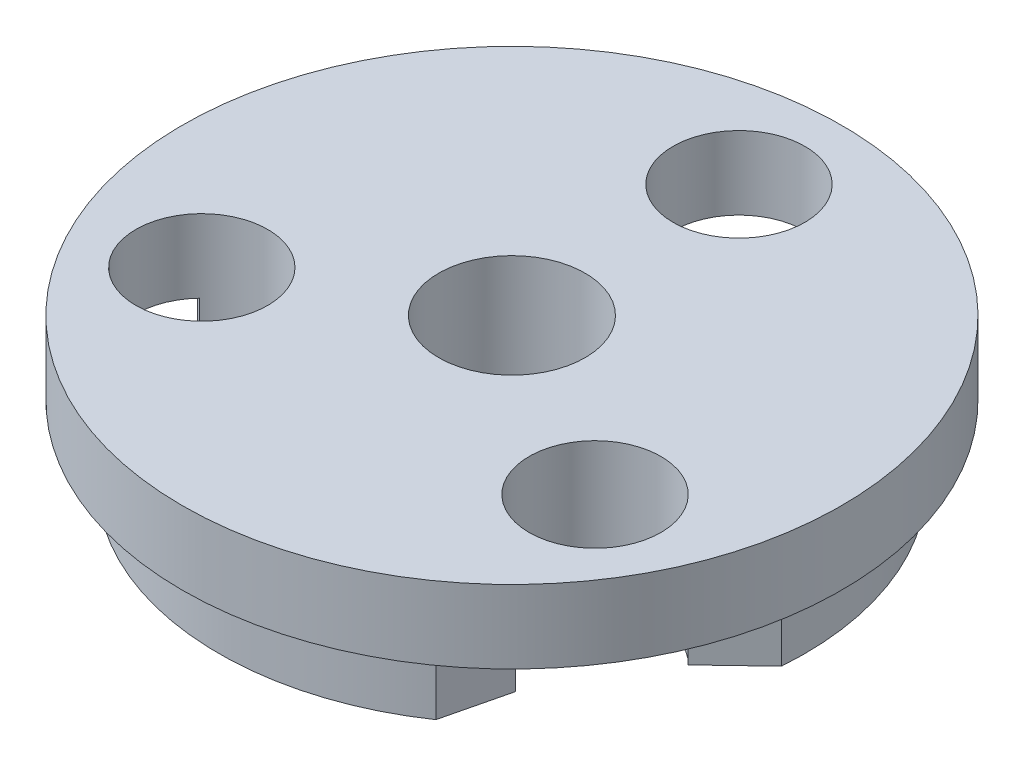
SolidWorks part; units mm, degrees
ref_plane "Front Plane" through (0, 0, 0) normal (0, 0, 1) x (1, 0, 0)
ref_plane "Top Plane" through (0, 0, 0) normal (0, 1, 0) x (1, 0, 0)
ref_plane "Right Plane" through (0, 0, 0) normal (1, 0, 0) x (0, 0, -1)
sketch "Sketch1" plane through (0, 0, 0) normal (0, 1, 0) x (1, 0, 0)
  circle A0 centre (0, 0) radius 22.5
  dimension "D1" = 45
extrude "Boss-Extrude1" add sketch "Sketch1" along normal mid plane 7
sketch "Sketch2" plane through (0, 3.5, 0) normal (0, 1, 0) x (1, 0, 0)
  circle A0 centre (0, 15.5) radius 9
  circle A2 centre (13.4234, -7.75) radius 9
  circle A3 centre (-13.4234, -7.75) radius 9
  point P10 (0, 0)
  dimension "D1" = 18
  dimension "D2" = 3
  dimension "D3" = 15.5
sketch "Sketch7" plane through (0, 3.5, 0) normal (0, 1, 0) x (1, 0, 0)
  circle A0 centre (0, 0) radius 5
  dimension "D1" = 10
extrude "Cut-Extrude1" cut sketch "Sketch2" against normal through all
extrude "Cut-Extrude2" cut sketch "Sketch7" against normal through all
sketch "Sketch8" plane through (0, -3.5, 0) normal (0, -1, 0) x (1, 0, 0)
  circle A0 centre (0, 0) radius 20
  arc A6 (-21.9601, 4.8995) -> (-6.7369, -21.4677) centre (0, 0) ccw
  arc A7 (6.7369, -21.4677) -> (-6.7369, -21.4677) centre (0, -15.5) ccw
  arc A8 (6.7369, -21.4677) -> (21.9601, 4.8995) centre (0, 0) ccw
  arc A9 (15.2232, 16.5682) -> (21.9601, 4.8995) centre (13.4234, 7.75) ccw
  arc A10 (15.2232, 16.5682) -> (-15.2232, 16.5682) centre (0, 0) ccw
  arc A11 (-21.9601, 4.8995) -> (-15.2232, 16.5682) centre (-13.4234, 7.75) ccw
  arc A12 (-21.9601, 4.8995) -> (-6.7369, -21.4677) centre (0, 0) ccw
  arc A13 (6.7369, -21.4677) -> (-6.7369, -21.4677) centre (0, -15.5) ccw
  arc A14 (6.7369, -21.4677) -> (21.9601, 4.8995) centre (0, 0) ccw
  arc A15 (15.2232, 16.5682) -> (21.9601, 4.8995) centre (13.4234, 7.75) ccw
  arc A16 (15.2232, 16.5682) -> (-15.2232, 16.5682) centre (0, 0) ccw
  arc A17 (-21.9601, 4.8995) -> (-15.2232, 16.5682) centre (-13.4234, 7.75) ccw
  circle M7 centre (0, 0) radius 5
  arc M9 (-6.7369, -21.4677) -> (6.7369, -21.4677) centre (0, -15.5) cw
  arc M11 (21.9601, 4.8995) -> (15.2232, 16.5682) centre (13.4234, 7.75) cw
  arc M13 (-15.2232, 16.5682) -> (-21.9601, 4.8995) centre (-13.4234, 7.75) cw
  dimension "D2" = 40
  dimension "D1" = 0
extrude "Boss-Extrude2" add sketch "Sketch8" along normal blind 5 contours A0 M9 M11 M13 M7
sketch "Sketch9" plane through (0, -8.5, 0) normal (0, -1, 0) x (1, 0, 0)
  line L0 (-19.9404, 1.5429) -> (-16.6819, 4.6464)
  line L1 (-12.3649, 12.1237) -> (-11.3064, 16.4975)
  line L4 (11.3064, 16.4975) -> (12.3649, 12.1237)
  line L5 (16.6819, 4.6464) -> (19.9404, 1.5429)
  arc A3 (11.3064, 16.4975) -> (19.9404, 1.5429) centre (13.4234, 7.75) ccw construction
  arc A7 (-19.9404, 1.5429) -> (-11.3064, 16.4975) centre (-13.4234, 7.75) ccw construction
  arc A8 (11.3064, 16.4975) -> (19.9404, 1.5429) centre (13.4234, 7.75) ccw
  arc A9 (-19.9404, 1.5429) -> (-11.3064, 16.4975) centre (-13.4234, 7.75) ccw
  arc A10 (-16.6819, 4.6464) -> (-12.3649, 12.1237) centre (-13.4234, 7.75) ccw
  arc A11 (12.3649, 12.1237) -> (16.6819, 4.6464) centre (13.4234, 7.75) ccw
  dimension "D1" = 9
extrude "Boss-Extrude4" add sketch "Sketch9" against normal blind 5
sketch "Sketch10" plane through (0, 3.5, 0) normal (0, 1, 0) x (1, 0, 0)
  arc A6 (-6.7369, 21.4677) -> (6.7369, 21.4677) centre (0, 15.5) ccw
  arc A7 (-6.7369, 21.4677) -> (-21.9601, -4.8995) centre (0, 0) ccw
  arc A8 (-15.2232, -16.5682) -> (-21.9601, -4.8995) centre (-13.4234, -7.75) ccw
  arc A9 (-15.2232, -16.5682) -> (15.2232, -16.5682) centre (0, 0) ccw
  arc A10 (21.9601, -4.8995) -> (15.2232, -16.5682) centre (13.4234, -7.75) ccw
  arc A11 (21.9601, -4.8995) -> (6.7369, 21.4677) centre (0, 0) ccw
  arc A12 (-6.7369, 21.4677) -> (6.7369, 21.4677) centre (0, 15.5) ccw
  arc A13 (-6.7369, 21.4677) -> (-21.9601, -4.8995) centre (0, 0) ccw
  arc A14 (-15.2232, -16.5682) -> (-21.9601, -4.8995) centre (-13.4234, -7.75) ccw
  arc A15 (-15.2232, -16.5682) -> (15.2232, -16.5682) centre (0, 0) ccw
  arc A16 (21.9601, -4.8995) -> (15.2232, -16.5682) centre (13.4234, -7.75) ccw
  arc A17 (21.9601, -4.8995) -> (6.7369, 21.4677) centre (0, 0) ccw
  dimension "D1" = 0
extrude "Cut-Extrude3" cut sketch "Sketch10" against normal blind 7
sketch "Sketch15" plane through (0, -3.5, 0) normal (0, 1, 0) x (1, 0, 0)
  circle A0 centre (0, 0) radius 22.5
  arc A1 (-12.3649, -12.1237) -> (-16.6819, -4.6464) centre (-13.4234, -7.75) ccw construction
  arc A2 (16.6819, -4.6464) -> (12.3649, -12.1237) centre (13.4234, -7.75) ccw construction
  arc A3 (-8.634, 18.0403) -> (8.634, 18.0403) centre (0, 15.5) ccw construction
  arc A4 (-12.3649, -12.1237) -> (-16.6819, -4.6464) centre (-13.4234, -7.75) ccw
  arc A5 (16.6819, -4.6464) -> (12.3649, -12.1237) centre (13.4234, -7.75) ccw
  arc A6 (-8.634, 18.0403) -> (8.634, 18.0403) centre (0, 15.5) ccw
  circle A7 centre (-13.4234, -7.75) radius 4.5
  circle A8 centre (0, 15.5) radius 4.5
  circle A9 centre (13.4234, -7.75) radius 4.5
  arc M2 (-16.6819, -4.6464) -> (-12.3649, -12.1237) centre (-13.4234, -7.75) cw
  line M3 (-12.3649, -12.1237) -> (-11.3064, -16.4975)
  arc M4 (-11.3064, -16.4975) -> (11.3064, -16.4975) centre (0, 0) ccw
  line M5 (11.3064, -16.4975) -> (12.3649, -12.1237)
  arc M6 (12.3649, -12.1237) -> (16.6819, -4.6464) centre (13.4234, -7.75) cw
  line M7 (16.6819, -4.6464) -> (19.9404, -1.5429)
  arc M8 (19.9404, -1.5429) -> (8.634, 18.0403) centre (0, 0) ccw
  arc M9 (8.634, 18.0403) -> (-8.634, 18.0403) centre (0, 15.5) cw
  arc M10 (-8.634, 18.0403) -> (-19.9404, -1.5429) centre (0, 0) ccw
  line M11 (-19.9404, -1.5429) -> (-16.6819, -4.6464)
  circle M12 centre (0, 0) radius 5
  dimension "D1" = 45
  dimension "D2" = 9
extrude "Boss-Extrude8" add sketch "Sketch15" along normal blind 5 contours M11 M2 M3 M4 M5 M6 M7 M8 M9 M10 M12 | A0 A9 A7 A8 M5 M4 M3 M11 M10 M9 M8 M7
